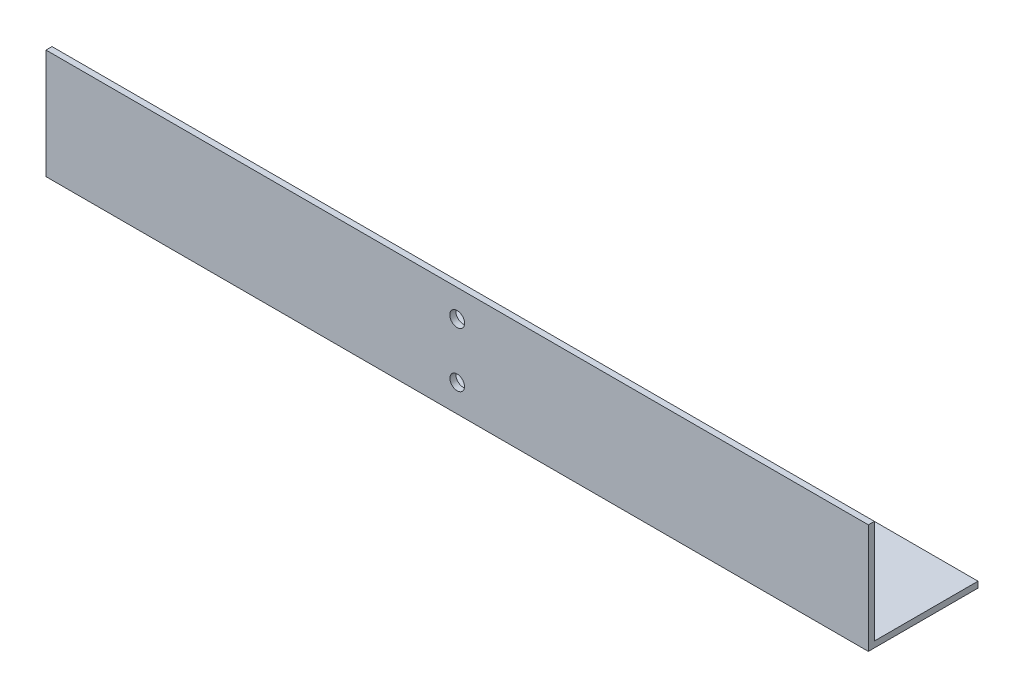
SolidWorks part; units mm, degrees
ref_plane "Front Plane" through (0, 0, 0) normal (0, 0, 1) x (1, 0, 0)
ref_plane "Top Plane" through (0, 0, 0) normal (0, 1, 0) x (1, 0, 0)
ref_plane "Right Plane" through (0, 0, 0) normal (1, 0, 0) x (0, 0, -1)
sketch "Sketch1" plane through (0, 0, 0) normal (0, 1, 0) x (1, 0, 0)
  line L1 (-190.5, 25.4) -> (190.5, 25.4)
  line L2 (-190.5, 25.4) -> (-190.5, -25.4)
  line L3 (-190.5, -25.4) -> (190.5, -25.4)
  line L4 (190.5, 25.4) -> (190.5, -25.4)
  line L5 (-190.5, 25.4) -> (190.5, -25.4) construction
  line L6 (-190.5, -25.4) -> (190.5, 25.4) construction
  point P0 (0, 0)
  dimension "D1" = 50.8
  dimension "D2" = 381
extrude "Boss-Extrude1" add sketch "Sketch1" along normal blind 2.794
sketch "Sketch2" plane through (0, 2.794, 0) normal (0, 1, 0) x (1, 0, 0)
  line L0 (190.5, -25.4) -> (190.5, 25.4) construction
  line L1 (-190.5, -25.4) -> (190.5, -25.4)
  line L2 (-190.5, -25.4) -> (-190.5, -22.606)
  line L3 (-190.5, -22.606) -> (190.5, -22.606)
  line L4 (190.5, -25.4) -> (190.5, -22.606)
  dimension "D1" = 2.794
extrude "Boss-Extrude2" add sketch "Sketch2" along normal blind 48.006
sketch "Sketch3" plane through (0, 0, 25.4) normal (0, 0, 1) x (1, 0, 0)
  line L0 (0, 50.8) -> (0, 0) construction
  line L1 (-190.5, 50.8) -> (190.5, 50.8) construction
  circle A0 centre (0, 38.1) radius 3.429
  circle A1 centre (0, 12.7) radius 3.3734
  point P9 (0, 25.4)
  dimension "D1" = 6.7469
  dimension "D2" = 6.858
  dimension "D3" = 12.7
  dimension "D4" = 12.7
extrude "Cut-Extrude1" cut sketch "Sketch3" against normal up to surface (2.794 mm away) up to face at (0, 26.797, 22.606)
